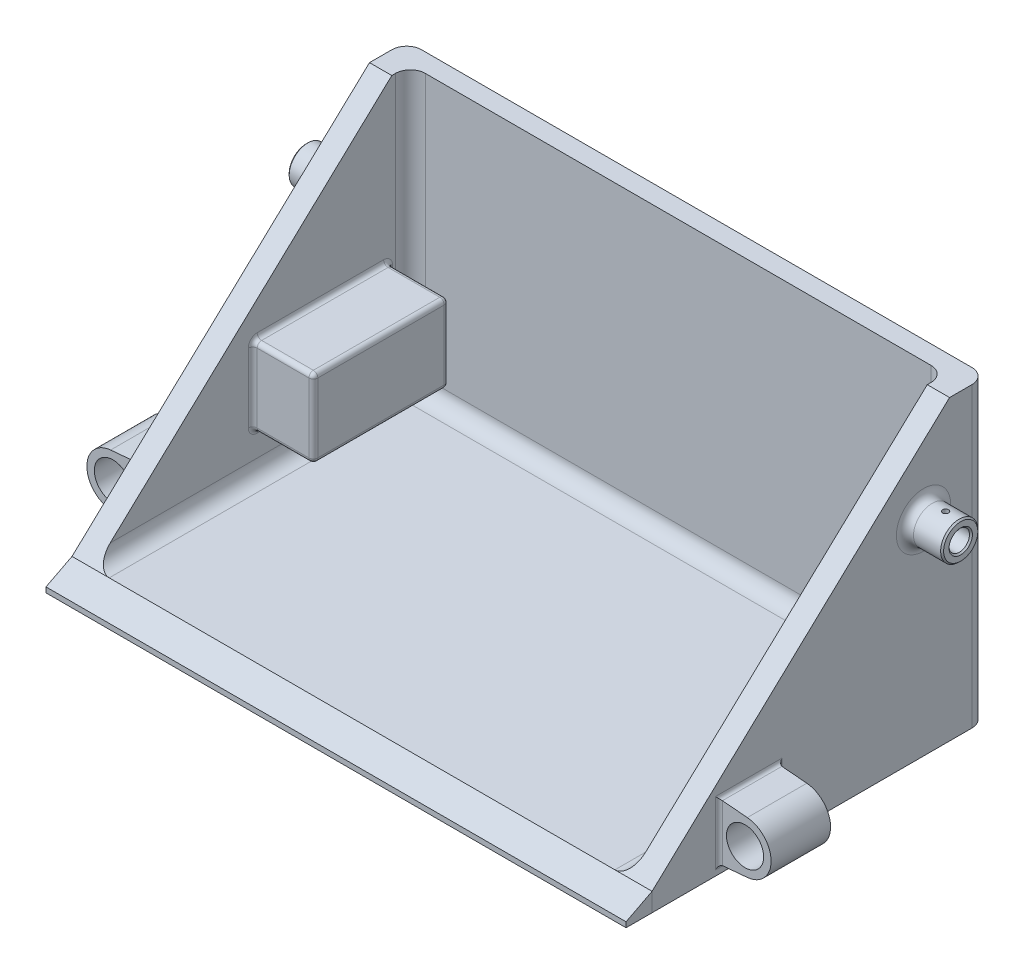
SolidWorks part; units mm, degrees
ref_plane "Front Plane" through (0, 0, 0) normal (0, 0, 1) x (1, 0, 0)
ref_plane "Top Plane" through (0, 0, 0) normal (0, 1, 0) x (1, 0, 0)
ref_plane "Right Plane" through (0, 0, 0) normal (1, 0, 0) x (0, 0, -1)
sketch "Sketch1" plane through (0, 0, 0) normal (0, 1, 0) x (1, 0, 0)
  line L1 (-99.06, 57.15) -> (99.06, 57.15)
  line L2 (-99.06, 57.15) -> (-99.06, -57.15)
  line L3 (-99.06, -57.15) -> (99.06, -57.15)
  line L4 (99.06, 57.15) -> (99.06, -57.15)
  line L5 (-99.06, 57.15) -> (99.06, -57.15) construction
  line L6 (-99.06, -57.15) -> (99.06, 57.15) construction
  point P0 (0, 0)
  dimension "D1" = 198.12
  dimension "D2" = 114.3
extrude "Boss-Extrude1" add sketch "Sketch1" along normal mid plane 6.35
sketch "Sketch3" plane through (-99.06, 0, 0) normal (-1, 0, 0) x (0, 0, 1)
  line L0 (-57.15, 3.175) -> (-57.15, 98.425)
  line L1 (-57.15, 98.425) -> (-44.45, 98.425)
  line L2 (-44.45, 98.425) -> (57.15, 3.175)
  line L3 (57.15, 3.175) -> (-57.15, 3.175)
  line L4 (-57.15, -3.175) -> (57.15, -3.175) construction
  dimension "D1" = 101.6
  dimension "D2" = 12.7
extrude "Boss-Extrude2" add sketch "Sketch3" against normal blind 7.62
mirror "Mirror1" about plane through (0, 0, 0) normal (1, 0, 0) of "Boss-Extrude2"
sketch "Sketch4" plane through (0, 3.175, 0) normal (0, 1, 0) x (1, 0, 0)
  line L0 (-91.44, 57.15) -> (91.44, 57.15)
  line L1 (91.44, 57.15) -> (91.44, 50.8)
  line L2 (91.44, 50.8) -> (-91.44, 50.8)
  line L3 (-91.44, 50.8) -> (-91.44, 57.15)
  dimension "D1" = 6.35
extrude "Boss-Extrude3" add sketch "Sketch4" along normal up to surface (95.25 mm away) up to face at (-95.25, 98.425, -50.8)
sketch "Sketch5" plane through (-99.06, 0, 0) normal (-1, 0, 0) x (0, 0, 1)
  line L1 (66.04, -3.175) -> (57.15, -3.175)
  line L2 (57.15, -3.175) -> (57.15, 3.175)
  line L3 (-57.15, 98.425) -> (-57.15, -3.175) construction
  line L4 (57.15, 3.175) -> (66.04, -1.397)
  line L5 (66.04, -1.397) -> (66.04, -3.175)
  dimension "D1" = 123.19
  dimension "D2" = 1.778
extrude "Boss-Extrude4" add sketch "Sketch5" along direction (1, 0, 0) on the side against the normal up to surface (198.12 mm away) separate body
fillet "Fillet2" radius 5.08 5 edges at (91.44, 3.175, 3.175) (91.44, 50.8, -50.8) (0, 3.175, -50.8) (-91.44, 3.175, 3.175) (-91.44, 50.8, -50.8)
fillet "Fillet3" radius 5.08 2 edges at (99.06, 47.625, -57.15) (-99.06, 47.625, -57.15)
sketch "Sketch6" plane through (99.06, 0, 0) normal (1, 0, 0) x (0, 0, -1)
  line L0 (-57.15, -3.175) -> (52.07, -3.175) construction
  line L1 (57.15, 98.425) -> (57.15, -3.175) construction
  circle A0 centre (35.56, 66.675) radius 3.4925
  circle A1 centre (35.56, 66.675) radius 6.35
  dimension "D1" = 6.985
  dimension "D2" = 12.7
  dimension "D3" = 69.85
  dimension "D4" = 21.59
extrude "Boss-Extrude5" add sketch "Sketch6" along normal blind 12.7
mirror "Mirror2" about plane through (0, 0, 0) normal (1, 0, 0) of "Boss-Extrude5"
fillet "Fillet4" radius 2.921 2 edges at (-99.06, 66.675, -41.91) (99.06, 66.675, -29.21)
chamfer "Chamfer1" distance 0.508 angle 45 4 edges at (111.76, 66.675, -39.0525) (111.76, 66.675, -41.91) (-111.76, 66.675, -39.0525) (-111.76, 66.675, -41.91)
ref_plane "setscrew_lhs_plane" through (0, 73.025, 0) normal (0, 1, 0) x (1, 0, 0)
sketch "Sketch7" plane through (0, 73.025, 0) normal (0, 1, 0) x (1, 0, 0)
  line L0 (101.981, 29.21) -> (111.252, 29.21) construction
  line L1 (111.252, 41.91) -> (101.981, 41.91) construction
  line L2 (101.981, 29.21) -> (111.252, 29.21) construction
  line L3 (111.252, 41.91) -> (101.981, 41.91) construction
  line L4 (106.6165, 41.91) -> (106.6165, 29.21) construction
  circle A0 centre (106.6165, 35.56) radius 1.0033
  dimension "D1" = 2.0066
extrude "Cut-Extrude1" cut sketch "Sketch7" against normal blind 3.81
pattern_circular "CirPattern1" count 2 every 90 about axis through (111.76, 66.675, -35.56) along (-1, 0, 0) of "Cut-Extrude1"
mirror "Mirror3" about plane through (0, 0, 0) normal (1, 0, 0) of "CirPattern1", "Cut-Extrude1"
sketch "Sketch8" plane through (-99.06, 0, 0) normal (-1, 0, 0) x (0, 0, 1)
  line L0 (-57.15, -3.175) -> (-57.15, 98.425) construction
  line L1 (-40.64, 41.275) -> (0.508, 41.275)
  line L2 (-40.64, 41.275) -> (-40.64, 19.685)
  line L3 (-40.64, 19.685) -> (0.508, 19.685)
  line L4 (0.508, 41.275) -> (0.508, 19.685)
  line L5 (-40.64, 41.275) -> (0.508, 19.685) construction
  line L6 (-40.64, 19.685) -> (0.508, 41.275) construction
  line L7 (-52.07, -3.175) -> (57.15, -3.175) construction
  point P0 (-20.066, 30.48)
  dimension "D1" = 16.51
  dimension "D2" = 41.148
  dimension "D3" = 22.86
  dimension "D4" = 21.59
extrude "Cut-Extrude2" cut sketch "Sketch8" against normal up to surface (7.62 mm away) up to face at (-91.44, 53.34, -21.0397)
sketch "Sketch9" plane through (-91.44, 0, 0) normal (1, 0, 0) x (0, 0, -1)
  line L0 (40.64, 41.275) -> (40.64, 19.685) construction
  line L1 (-0.508, 19.685) -> (-0.508, 41.275) construction
  line L2 (-0.508, 41.275) -> (40.64, 41.275) construction
  line L3 (40.64, 19.685) -> (-0.508, 19.685) construction
  line L4 (40.64, 41.275) -> (40.64, 19.685)
  line L5 (-0.508, 19.685) -> (-0.508, 41.275)
  line L6 (-0.508, 41.275) -> (40.64, 41.275)
  line L7 (40.64, 19.685) -> (-0.508, 19.685)
  line L8 (40.64, 30.48) -> (-0.508, 30.48) construction
  line L9 (20.066, 41.275) -> (20.066, 19.685) construction
  line L11 (-3.048, 17.145) -> (43.18, 17.145)
  line L12 (-3.048, 17.145) -> (-3.048, 43.815)
  line L13 (-3.048, 43.815) -> (43.18, 43.815)
  line L14 (43.18, 17.145) -> (43.18, 43.815)
  line L15 (-3.048, 17.145) -> (43.18, 43.815) construction
  line L16 (-3.048, 43.815) -> (43.18, 17.145) construction
  point P8 (20.066, 30.48)
  dimension "D1" = 2.54
  dimension "D2" = 2.54
extrude "Boss-Extrude6" add sketch "Sketch9" along normal blind 17.78
sketch "Sketch10" plane through (-73.66, 0, 0) normal (1, 0, 0) x (0, 0, -1)
  line L4 (43.18, 17.145) -> (43.18, 43.815)
  line L5 (43.18, 43.815) -> (-3.048, 43.815)
  line L6 (-3.048, 43.815) -> (-3.048, 17.145)
  line L7 (-3.048, 17.145) -> (43.18, 17.145)
  line L8 (43.18, 17.145) -> (43.18, 43.815)
  line L9 (43.18, 43.815) -> (-3.048, 43.815)
  line L10 (-3.048, 43.815) -> (-3.048, 17.145)
  line L11 (-3.048, 17.145) -> (43.18, 17.145)
  dimension "D1" = 0
extrude "Boss-Extrude7" add sketch "Sketch10" along normal blind 2.921
fillet "Fillet5" radius 1.524 12 edges at (-91.44, 30.48, 3.048) (-81.0895, 43.815, 3.048) (-91.44, 43.815, -20.066) (-70.739, 30.48, 3.048) (-70.739, 43.815, -20.066) (-70.739, 30.48, -43.18) (-81.0895, 43.815, -43.18) (-91.44, 30.48, -43.18) (-81.0895, 17.145, 3.048) (-70.739, 17.145, -20.066) (-81.0895, 17.145, -43.18) (-91.44, 17.145, -20.066)
fillet "Fillet6" radius 1.524 4 edges at (-86.36, 19.685, -40.64) (-86.36, 19.685, 0.508) (-86.36, 41.275, 0.508) (-86.36, 41.275, -40.64)
sketch "Sketch11" plane through (-99.06, 0, 0) normal (-1, 0, 0) x (0, 0, 1)
  line L0 (-20.066, 41.275) -> (-20.066, 19.685) construction
  line L1 (-39.116, 41.275) -> (-1.016, 41.275) construction
  line L2 (-1.016, 19.685) -> (-39.116, 19.685) construction
  line L3 (0.508, 30.48) -> (-40.64, 30.48) construction
  line L4 (0.508, 39.751) -> (0.508, 21.209) construction
  line L5 (-40.64, 21.209) -> (-40.64, 39.751) construction
  line L11 (-45.085, 35.56) -> (4.953, 35.56) construction
  line L12 (-40.64, 39.751) -> (-40.64, 21.209) construction
  line L13 (-40.64, 38.735) -> (-40.64, 22.225)
  line L14 (-40.64, 38.735) -> (-48.26, 38.735)
  line L15 (-48.26, 38.735) -> (-48.26, 22.225)
  line L16 (-48.26, 22.225) -> (-40.64, 22.225)
  line L17 (0.508, 38.735) -> (8.128, 38.735)
  line L18 (8.128, 38.735) -> (8.128, 22.225)
  line L19 (0.508, 38.735) -> (0.508, 22.225)
  line L20 (8.128, 22.225) -> (0.508, 22.225)
  circle A2 centre (-45.085, 35.56) radius 1.524
  circle A3 centre (4.953, 35.56) radius 1.524
  circle A4 centre (4.953, 25.4) radius 1.524
  circle A5 centre (-45.085, 25.4) radius 1.524
  point P16 (-20.066, 35.56)
  point P23 (-40.64, 30.48)
  dimension "D2" = 3.048
  dimension "D3" = 3.048
  dimension "D4" = 50.038
  dimension "D5" = 10.16
  dimension "D1" = 16.51
  dimension "D6" = 7.62
extrude "Boss-Extrude8" add sketch "Sketch11" along normal blind 3.81
ref_plane "Plane1" through (0, 0, -20.066) normal (0, 0, 1) x (1, 0, 0)
ref_plane "Plane2" through (0, 30.48, 0) normal (0, -1, 0) x (-1, 0, 0)
fillet "Fillet7" radius 1.27 10 edges at (-99.06, 39.243, -40.64) (-99.06, 21.717, 0.508) (-99.06, 21.717, -40.64) (-99.06, 38.735, -44.45) (-99.06, 30.48, -48.26) (-99.06, 22.225, -44.45) (-99.06, 39.243, 0.508) (-99.06, 22.225, 4.318) (-99.06, 30.48, 8.128) (-99.06, 38.735, 4.318)
ref_plane "Plane3" through (0, 0, 24.13) normal (0, 0, -1) x (-1, 0, 0)
ref_plane "Plane4" through (0, 0, -6.35) normal (0, 0, -1) x (-1, 0, 0)
sketch "Sketch12" plane through (0, 0, 24.13) normal (0, 0, -1) x (-1, 0, 0)
  line L0 (99.06, 98.425) -> (99.06, -3.175) construction
  line L1 (-93.98, -3.175) -> (93.98, -3.175) construction
  line L2 (108.7248, 18.3812) -> (99.06, 19.2267)
  line L3 (108.7248, 0.6688) -> (99.06, -0.1767)
  line L4 (107.95, 9.525) -> (99.06, 9.525) construction
  line L5 (99.06, 19.2267) -> (99.06, -0.1767)
  circle A0 centre (107.95, 9.525) radius 6.35
  arc A1 (108.7248, 0.6688) -> (108.7248, 18.3812) centre (107.95, 9.525) ccw
  dimension "D1" = 12.7
  dimension "D2" = 17.78
  dimension "D5" = 5
  dimension "D3" = 8.89
  dimension "D4" = 12.7
  dimension "D6" = 5
extrude "Boss-Extrude9" add sketch "Sketch12" along normal mid plane 20.32
mirror "Mirror4" about plane through (0, 0, 0) normal (1, 0, 0) of "Boss-Extrude9"
fillet "Fillet8" radius 1.27 8 edges at (-99.06, 9.525, 13.97) (-99.06, 9.525, 34.29) (-99.06, 19.2267, 24.13) (-99.06, -0.1767, 24.13) (99.06, 9.525, 13.97) (99.06, -0.1767, 24.13) (99.06, 19.2267, 24.13) (99.06, 9.525, 34.29)
equation "\"D3@Sketch11\"=\"D2@Sketch11\""
